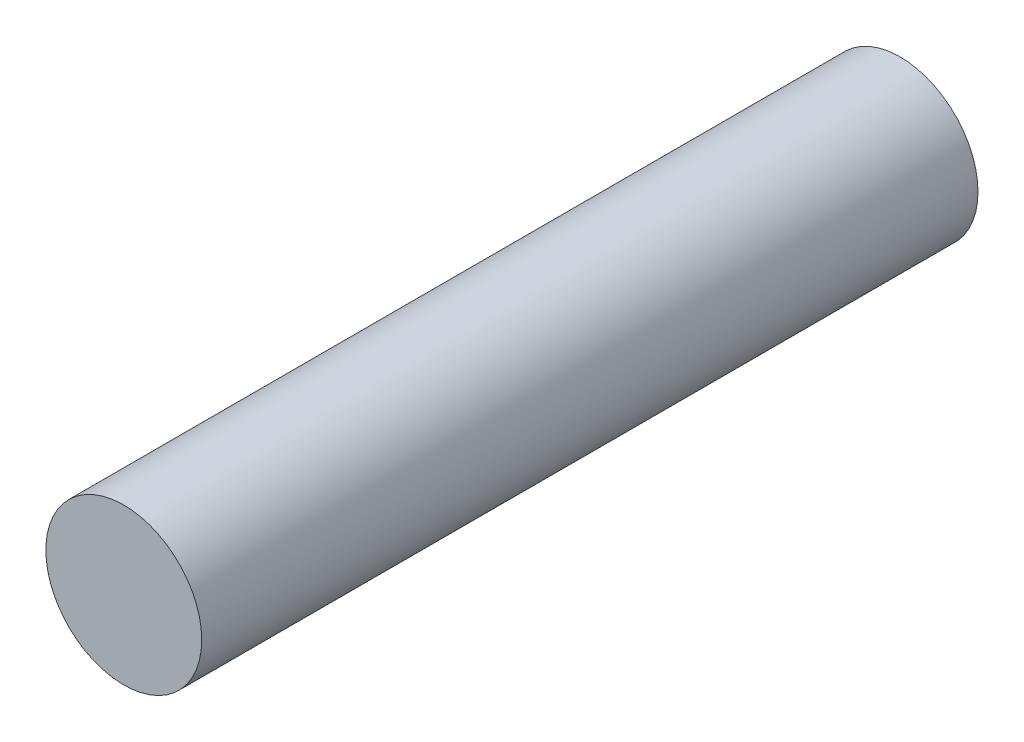
SolidWorks part; units mm, degrees
material "ABS PC"
ref_plane "Front Plane" through (0, 0, 0) normal (0, 0, 1) x (1, 0, 0)
ref_plane "Top Plane" through (0, 0, 0) normal (0, 1, 0) x (1, 0, 0)
ref_plane "Right Plane" through (0, 0, 0) normal (1, 0, 0) x (0, 0, -1)
sketch "Sketch1" plane through (0, 0, 0) normal (0, 0, 1) x (1, 0, 0)
  circle A0 centre (0, 0) radius 3.1877
  dimension "D1" = 6.3754
extrude "Boss-Extrude1" add sketch "Sketch1" along normal blind 31.75
